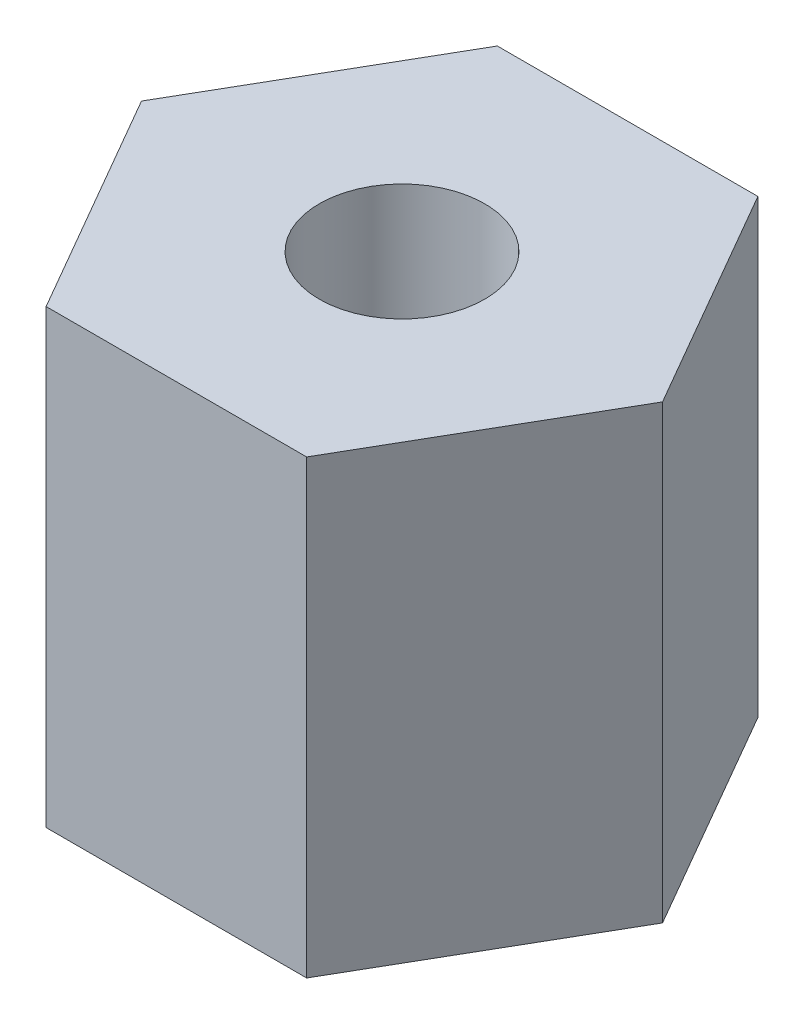
SolidWorks part; units mm, degrees
ref_plane "Front Plane" through (0, 0, 0) normal (0, 0, 1) x (1, 0, 0)
ref_plane "Top Plane" through (0, 0, 0) normal (0, 1, 0) x (1, 0, 0)
ref_plane "Right Plane" through (0, 0, 0) normal (1, 0, 0) x (0, 0, -1)
sketch "Sketch1" plane through (0, 0, 0) normal (0, 1, 0) x (1, 0, 0)
  line L1 (3.4641, 0) -> (1.7321, 3)
  line L2 (1.7321, 3) -> (-1.7321, 3)
  line L3 (-1.7321, 3) -> (-3.4641, 0)
  line L4 (-3.4641, 0) -> (-1.7321, -3)
  line L5 (-1.7321, -3) -> (1.7321, -3)
  line L6 (1.7321, -3) -> (3.4641, 0)
  circle A0 centre (0, 0) radius 3 construction
  circle A1 centre (0, 0) radius 1.1
  dimension "D2" = 2.2
  dimension "D1" = 6
extrude "Boss-Extrude1" add sketch "Sketch1" along normal blind 6
